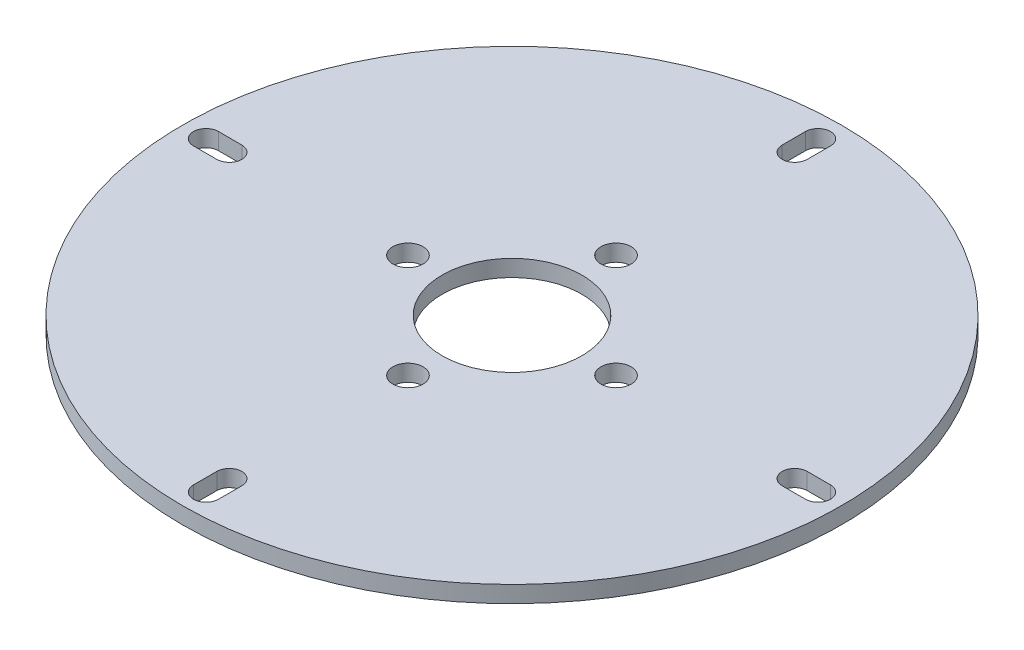
SolidWorks part; units mm, degrees
ref_plane "Front Plane" through (0, 0, 0) normal (0, 0, 1) x (1, 0, 0)
ref_plane "Top Plane" through (0, 0, 0) normal (0, 1, 0) x (1, 0, 0)
ref_plane "Right Plane" through (0, 0, 0) normal (1, 0, 0) x (0, 0, -1)
sketch "Sketch2" plane through (0, 0, 0) normal (0, 1, 0) x (1, 0, 0)
  circle A0 centre (0, 0) radius 125.73
  circle A1 centre (0, 116.7432) radius 4.7625
  circle A2 centre (116.7432, 0) radius 4.7625
  circle A3 centre (0, -116.7432) radius 4.7625
  circle A4 centre (-116.7432, 0) radius 4.7625
  circle A5 centre (0, 39.6875) radius 5.9531
  circle A6 centre (39.6875, 0) radius 5.9531
  circle A7 centre (0, -39.6875) radius 5.9531
  circle A8 centre (-39.6875, 0) radius 5.9531
  point P14 (0, 0)
  point P23 (0, 0)
  dimension "D1" = 251.46
  dimension "D2" = 9.525
  dimension "D5" = 11.9062
  dimension "D3" = 116.7432
  dimension "D6" = 39.6875
  dimension "D4" = 4
  dimension "D7" = 4
extrude "Boss-Extrude1" add sketch "Sketch2" along normal blind 6.35 contours A0
sketch "Sketch3" plane through (0, 6.35, 0) normal (0, 1, 0) x (1, 0, 0)
  line L0 (-4.7625, 107.8535) -> (-4.7625, 116.7435)
  line L1 (4.7625, 107.8535) -> (4.7625, 116.7435)
  line L2 (107.8535, 4.7625) -> (116.7435, 4.7625)
  line L3 (107.8535, -4.7625) -> (116.7435, -4.7625)
  line L4 (4.7626, -107.8535) -> (4.7626, -116.7435)
  line L5 (-4.7624, -107.8535) -> (-4.7624, -116.7435)
  line L6 (-107.8534, -4.7625) -> (-116.7434, -4.7625)
  line L7 (-107.8534, 4.7625) -> (-116.7434, 4.7625)
  arc A0 (4.7625, 116.7435) -> (-4.7625, 116.7435) centre (0, 116.7435) ccw
  arc A1 (116.7435, -4.7625) -> (116.7435, 4.7625) centre (116.7435, 0) ccw
  arc A2 (-4.7624, -116.7435) -> (4.7626, -116.7435) centre (0.0001, -116.7435) ccw
  arc A3 (-116.7434, 4.7625) -> (-116.7434, -4.7625) centre (-116.7434, 0) ccw
  circle A4 centre (0, 39.6875) radius 5.7547
  circle A5 centre (39.6875, 0) radius 5.7547
  circle A6 centre (0, -39.6875) radius 5.7547
  circle A7 centre (-39.6875, 0) radius 5.7547
  circle A8 centre (0, 0) radius 26.67
  arc A9 (-4.7625, 107.8535) -> (4.7625, 107.8535) centre (0, 107.8535) ccw
  arc A10 (107.8535, 4.7625) -> (107.8535, -4.7625) centre (107.8535, 0) ccw
  arc A11 (4.7626, -107.8535) -> (-4.7624, -107.8535) centre (0.0001, -107.8535) ccw
  arc A12 (-107.8534, -4.7625) -> (-107.8534, 4.7625) centre (-107.8534, 0) ccw
  point P12 (0, 0)
  point P21 (0, 0)
  dimension "D1" = 9.525
  dimension "D4" = 11.5094
  dimension "D6" = 4
  dimension "D7" = 53.34
  dimension "D8" = 165.1002
  dimension "D9" = 79.375
  dimension "D2" = 116.7435
  dimension "D5" = 39.6875
  dimension "D10" = 8.89
  dimension "D11" = 8.89
  dimension "D12" = 8.89
  dimension "D3" = 4
extrude "Cut-Extrude1" cut sketch "Sketch3" against normal blind 6.35
